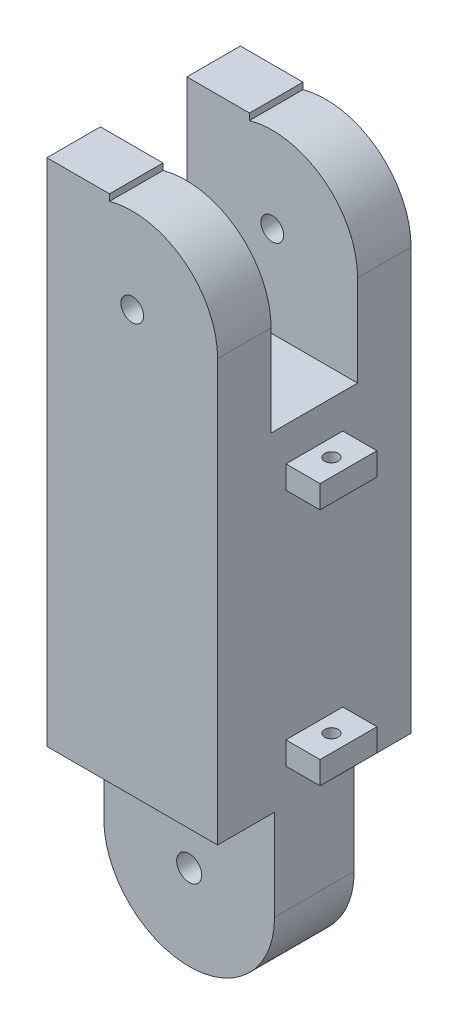
SolidWorks part; units mm, degrees
ref_plane "Front Plane" through (0, 0, 0) normal (0, 0, 1) x (1, 0, 0)
ref_plane "Top Plane" through (0, 0, 0) normal (0, 1, 0) x (1, 0, 0)
ref_plane "Right Plane" through (0, 0, 0) normal (1, 0, 0) x (0, 0, -1)
sketch "Finger_Skeleton" plane through (0, 0, 0) normal (0, 0, -1) x (-1, 0, 0)
  line L0 (0, 0) -> (0, 45)
  line L1 (0, 45) -> (0, 70)
  line L2 (0, 70) -> (0, 93)
  circle A1 centre (0, 0) radius 5 construction
  circle A2 centre (0, 45) radius 5 construction
  circle A3 centre (0, 70) radius 5 construction
  dimension "D4" = 10
  dimension "D5" = 10
  dimension "D6" = 10
  dimension "D1" = 45
  dimension "D2" = 25
  dimension "D3" = 23
sketch "Link1_Outline" plane through (0, 0, 0) normal (0, 0, 1) x (1, 0, 0)
  line L0 (0, 0) -> (0, 45) construction
  line L1 (-7.5, 0) -> (-7.5, 45)
  line L2 (7.5, 0) -> (7.5, 45)
  arc A0 (-7.5, 0) -> (7.5, 0) centre (0, 0) ccw
  arc A1 (7.5, 45) -> (-7.5, 45) centre (0, 45) ccw
  point P4 (0, 22.5)
  dimension "D1" = 15
extrude "Link1_Body" add sketch "Link1_Outline" along normal mid plane 17
sketch "Sketch1" plane through (7.5, 0, 0) normal (1, 0, 0) x (0, 0, -1)
  line L0 (0, 0) -> (0, 45) construction
  line L1 (3.5, -8) -> (9, -8)
  line L2 (3.5, -8) -> (3.5, 7.9981)
  line L3 (3.5, 7.9981) -> (9, 7.9981)
  line L4 (9, -8) -> (9, 7.9981)
  line L5 (-8.5, -7.5) -> (8.5, -7.5) construction
  line L6 (0, 8.25) -> (0, -8.25) construction
  line L7 (-9, -8) -> (-9, 7.9981)
  line L8 (-3.5, 7.9981) -> (-9, 7.9981)
  line L9 (-3.5, -8) -> (-3.5, 7.9981)
  line L10 (-3.5, -8) -> (-9, -8)
  dimension "D1" = 3.5
  dimension "D2" = 5.5
  dimension "D3" = 15.9981
  dimension "D4" = 0.5
extrude "Tongue_Cut" cut sketch "Sketch1" against normal through all both and the other way through all
sketch "Sketch7" plane through (0, 0, 0) normal (0, 0, 1) x (1, 0, 0)
  line L1 (-7.5, 45) -> (-2, 45)
  line L2 (-7.5, 45) -> (-7.5, 52.8)
  line L3 (-7.5, 52.8) -> (-2, 52.8)
  line L4 (-2, 45) -> (-2, 52.8)
  dimension "D1" = 5.5
  dimension "D2" = 7.8
extrude "Boss-Extrude1" add sketch "Sketch7" along normal mid plane 17
sketch "Sketch2" plane through (0, 0, 0) normal (1, 0, 0) x (0, 0, -1)
  line L0 (0, 0) -> (0, 45) construction
  line L1 (3.8, 37) -> (-3.8, 37)
  line L2 (3.8, 37) -> (3.8, 55)
  line L3 (3.8, 55) -> (-3.8, 55)
  line L4 (-3.8, 37) -> (-3.8, 55)
  dimension "D1" = 3.8
  dimension "D2" = 18
  dimension "D3" = 7.6
  dimension "D4" = 37
extrude "Slot_Cut" cut sketch "Sketch2" against normal through all both and the other way through all
sketch "Sketch3" plane through (0, 0, 0) normal (0, 0, 1) x (1, 0, 0)
  circle A0 centre (0, 0) radius 1.1
  circle A1 centre (0, 45) radius 1
  dimension "D1" = 2.2
  dimension "D2" = 2
extrude "Pin_Holes" cut sketch "Sketch3" against normal through all both and the other way through all
sketch "Sketch4" plane through (0, 0, 0) normal (0, 0, 1) x (1, 0, 0)
  line L0 (0, 0) -> (0, 45) construction
  line L1 (7, 13) -> (10.5, 13)
  line L2 (7, 13) -> (7, 11)
  line L3 (7, 11) -> (10.5, 11)
  line L4 (10.5, 13) -> (10.5, 11)
  dimension "D1" = 7
  dimension "D2" = 3.5
  dimension "D3" = 11
  dimension "D4" = 2
extrude "Guide_Block_1" add sketch "Sketch4" along normal mid plane 5
sketch "Sketch5" plane through (0, 0, 0) normal (0, 0, 1) x (1, 0, 0)
  line L0 (0, 0) -> (0, 45) construction
  line L1 (7.0006, 32) -> (10.5006, 32)
  line L2 (7.0006, 32) -> (7.0006, 34)
  line L3 (7.0006, 34) -> (10.5006, 34)
  line L4 (10.5006, 32) -> (10.5006, 34)
  dimension "D1" = 7.0006
  dimension "D2" = 32
  dimension "D3" = 3.5
  dimension "D4" = 2
extrude "Guide_Block_2" add sketch "Sketch5" along normal mid plane 5
sketch "Sketch6" plane through (0, 0, 0) normal (0, 1, 0) x (1, 0, 0)
  line L0 (10.5006, -2.5) -> (7.5, -2.5) construction
  circle A0 centre (9, 0) radius 0.6
  dimension "D1" = 1.2
  dimension "D2" = 9
  dimension "D3" = 2.5
extrude "Cord_Guides" cut sketch "Sketch6" along normal through all both and the other way through all
